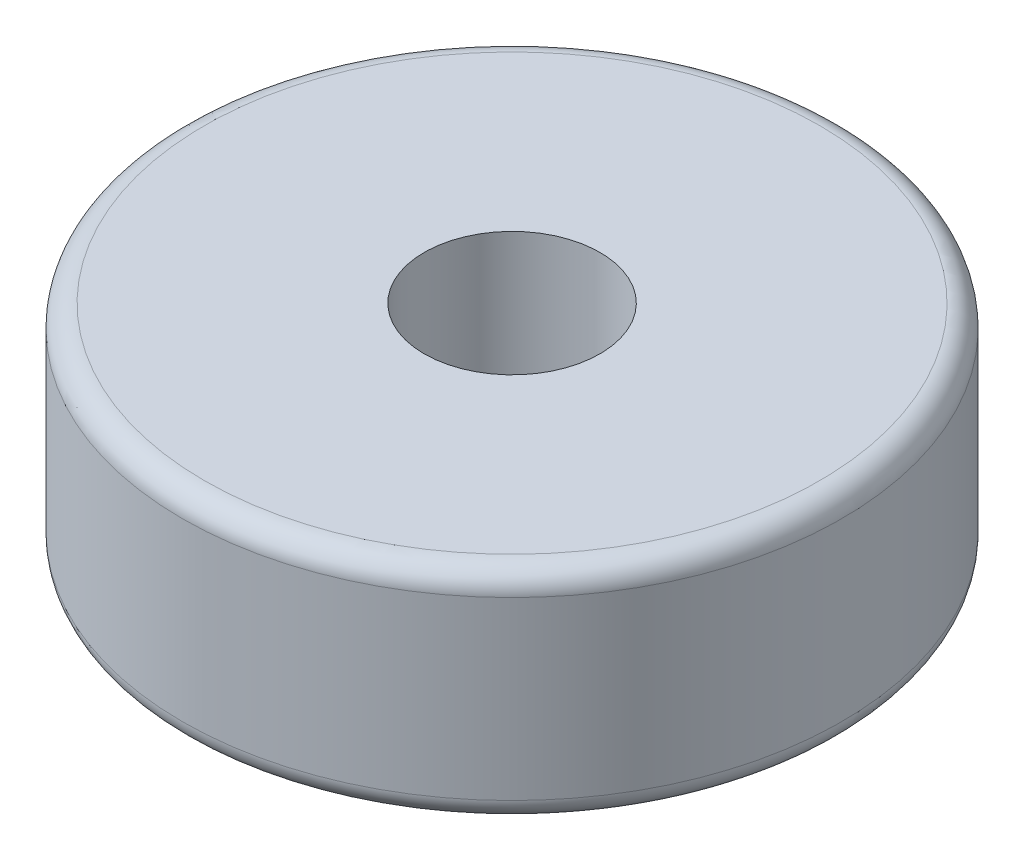
SolidWorks part; units mm, degrees
material "Rubber"
ref_plane "Front" through (0, 0, 0) normal (0, 0, 1) x (1, 0, 0)
ref_plane "Top" through (0, 0, 0) normal (0, 1, 0) x (1, 0, 0)
ref_plane "Right" through (0, 0, 0) normal (1, 0, 0) x (0, 0, -1)
sketch "Sketch2" plane through (0, 0, 0) normal (0, 1, 0) x (1, 0, 0)
  circle A0 centre (0, 0) radius 38.1
  circle A1 centre (0, 0) radius 10.16
  dimension "D1" = 76.2
  dimension "D2" = 20.32
extrude "Boss-Extrude1" add sketch "Sketch2" along normal blind 25.4
fillet "Fillet1" radius 2.54 2 edges at (0, 25.4, 38.1) (0, 0, 38.1)
